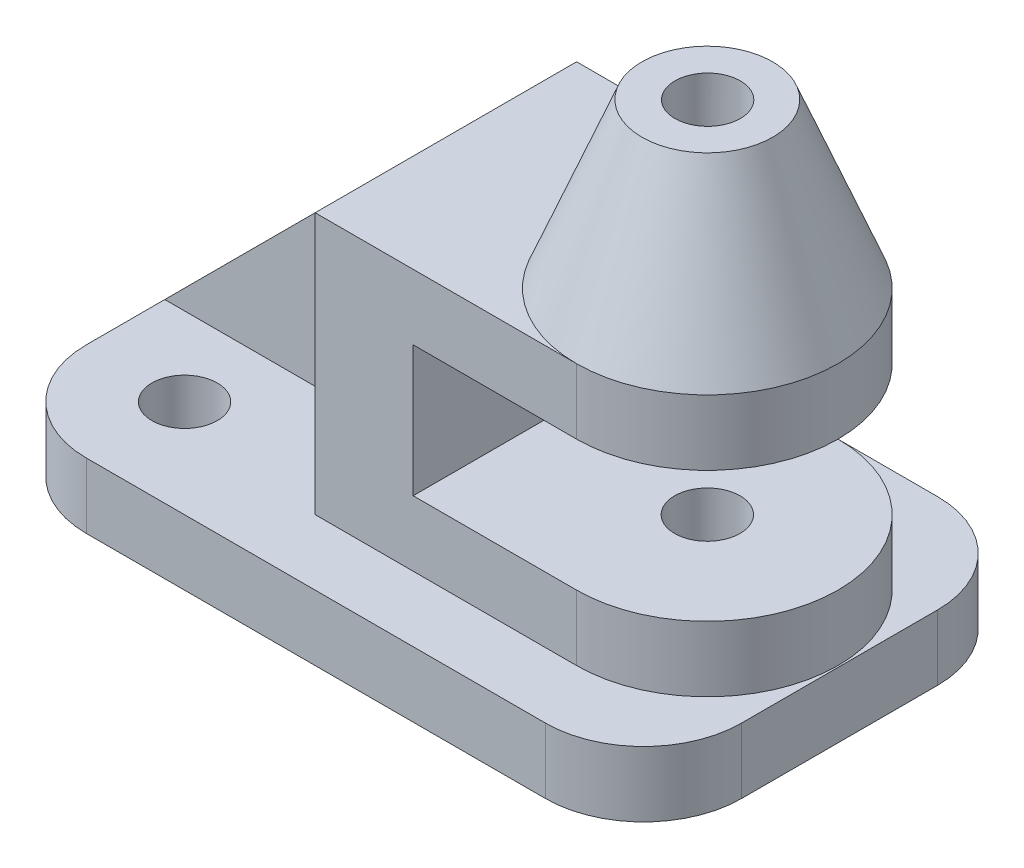
SolidWorks part; units mm, degrees
ref_plane "Front Plane" through (0, 0, 0) normal (0, 0, 1) x (1, 0, 0)
ref_plane "Top Plane" through (0, 0, 0) normal (0, 1, 0) x (1, 0, 0)
ref_plane "Right Plane" through (0, 0, 0) normal (1, 0, 0) x (0, 0, -1)
sketch "Sketch1" plane through (0, 0, 0) normal (0, 1, 0) x (1, 0, 0)
  line L0 (0, 42.7342) -> (0, -53.1033) construction
  line L5 (-74.3849, 0) -> (111.3896, 0) construction
  line L7 (-35.1191, -30) -> (35.1191, -30)
  line L8 (-50.1191, -15) -> (-50.1191, 15)
  line L9 (-35.1191, 30) -> (35.1191, 30)
  line L10 (50.1191, -15) -> (50.1191, 15)
  line L11 (-50.1191, -30) -> (50.1191, 30) construction
  line L12 (-50.1191, 30) -> (50.1191, -30) construction
  arc A4 (-35.1191, -30) -> (-50.1191, -15) centre (-35.1191, -15) cw
  arc A5 (35.1191, -30) -> (50.1191, -15) centre (35.1191, -15) ccw
  arc A6 (50.1191, 15) -> (35.1191, 30) centre (35.1191, 15) ccw
  arc A7 (-50.1191, 15) -> (-35.1191, 30) centre (-35.1191, 15) cw
  point P4 (0, 0)
  dimension "D1" = 15
extrude "Boss-Extrude4" add sketch "Sketch1" along normal blind 10 contours A7 L9 A6 L10 A5 L7 A4 L8
sketch "Sketch4" plane through (0, 10, 0) normal (0, 1, 0) x (1, 0, 0)
  line L0 (0, 35.0515) -> (0, -39.77) construction
  line L1 (-64.4858, 0) -> (65.7216, 0) construction
  circle A0 centre (-35.0547, 15.0385) radius 5
  circle A1 centre (-35.0547, -15.0385) radius 5
extrude "Cut-Extrude2" cut sketch "Sketch4" against normal blind 10 contours A0 | A1
sketch "Sketch5" plane through (0, 10, 0) normal (0, 1, 0) x (1, 0, 0)
  line L0 (0, 40.7145) -> (0, -42.7058) construction
  line L1 (-56.5603, 0) -> (90.5057, 0) construction
  line L2 (-10.1191, -20) -> (-10.1191, 20)
  line L3 (-10.1191, 20) -> (29.8809, 20)
  line L4 (-10.1191, -20) -> (29.8809, -20)
  arc A0 (29.8809, -20) -> (29.8809, 20) centre (29.8809, 0) ccw
  point P8 (-10.1191, 0)
extrude "Boss-Extrude5" add sketch "Sketch5" along normal blind 40
sketch "Sketch6" plane through (0, 50, 0) normal (0, 1, 0) x (1, 0, 0)
  circle A0 centre (29.8809, 0) radius 5
  circle A1 centre (29.8809, 0) radius 10
extrude "Cut-Extrude4" cut sketch "Sketch6" against normal blind 60 contours A0
sketch "Sketch7" plane through (0, 0, 20) normal (0, 0, 1) x (1, 0, 0)
  line L0 (-8.0326, 30) -> (59.8123, 30) construction
  line L1 (10.9985, 61.2087) -> (10.9985, 14.0015) construction
  line L2 (49.8809, 10) -> (49.8809, 50) construction
  line L3 (4.8809, 40) -> (49.8809, 40)
  line L4 (4.8809, 40) -> (4.8809, 20)
  line L5 (4.8809, 20) -> (49.8809, 20)
  line L6 (49.8809, 40) -> (49.8809, 20)
  line L7 (-10.1191, 50) -> (29.8809, 50) construction
  line L8 (-35.1191, 10) -> (35.1191, 10) construction
  line L9 (-10.1191, 50) -> (-10.1191, 10) construction
  dimension "D1" = 10
  dimension "D2" = 10
  dimension "D3" = 15
extrude "Cut-Extrude5" cut sketch "Sketch7" against normal blind 40 contours L4 L3 L6 L5
sketch "Sketch8" plane through (0, 0, 0) normal (0, 0, 1) x (1, 0, 0)
  line L0 (-50.1191, 10) -> (-10.1191, 50)
rib "Rib1" sketch "Sketch8" sketch "Sketch8" thickness 6 extrusion direction parallel to sketch draft on no parameters "D1"=6
sketch "Sketch9" plane through (0, 50, 0) normal (0, 1, 0) x (1, 0, 0)
  circle A0 centre (29.8809, 0) radius 20
extrude "Boss-Extrude7" add sketch "Sketch9" along normal blind 25 draft 21.8 contours A0
sketch "Sketch15" plane through (0, 75, 0) normal (0, 1, 0) x (1, 0, 0)
  circle A0 centre (29.9309, 0) radius 5
  point P1 (0, 0)
extrude "Cut-Extrude6" cut sketch "Sketch15" against normal blind 25 contours A0
